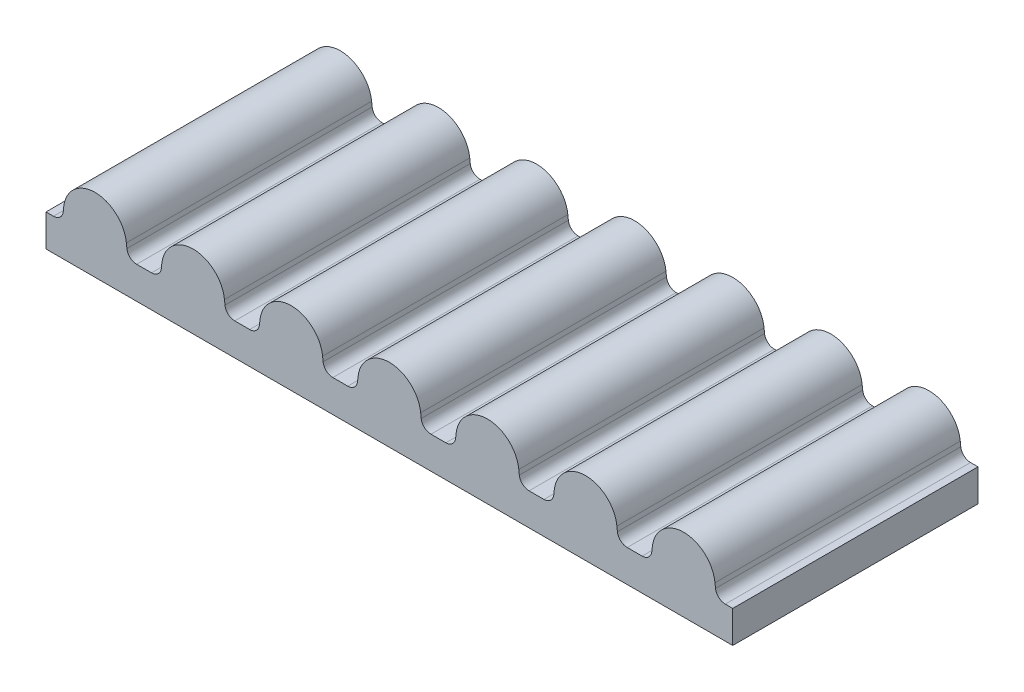
SolidWorks part; units mm, degrees
ref_plane "Front Plane" through (0, 0, 0) normal (0, 0, 1) x (1, 0, 0)
ref_plane "Top Plane" through (0, 0, 0) normal (0, 1, 0) x (1, 0, 0)
ref_plane "Right Plane" through (0, 0, 0) normal (1, 0, 0) x (0, 0, -1)
ref_plane "Plane4" through (0, 0, -10) normal (0, 0, -1) x (-1, 0, 0)
sketch "Sketch1" plane through (0, 0, -10) normal (0, 0, -1) x (-1, 0, 0)
  line L0 (0, 2.62) -> (-0.6084, 2.62)
  line L1 (-1.4036, 3.3322) -> (-1.4455, 3.7119)
  line L2 (-6.5545, 3.7119) -> (-6.5964, 3.3322)
  line L3 (-7.3916, 2.62) -> (-8.6084, 2.62)
  line L4 (-9.4036, 3.3322) -> (-9.4455, 3.7119)
  line L5 (-14.5545, 3.7119) -> (-14.5964, 3.3322)
  line L6 (-15.3916, 2.62) -> (-16.6084, 2.62)
  line L7 (-17.4036, 3.3322) -> (-17.4455, 3.7119)
  line L8 (-22.5545, 3.7119) -> (-22.5964, 3.3322)
  line L9 (-23.3916, 2.62) -> (-24.6084, 2.62)
  line L10 (-25.4036, 3.3322) -> (-25.4455, 3.7119)
  line L11 (-30.5545, 3.7119) -> (-30.5964, 3.3322)
  line L12 (-31.3916, 2.62) -> (-32.6084, 2.62)
  line L13 (-33.4036, 3.3322) -> (-33.4455, 3.7119)
  line L14 (-38.5545, 3.7119) -> (-38.5964, 3.3322)
  line L15 (-39.3916, 2.62) -> (-40.6084, 2.62)
  line L16 (-41.4036, 3.3322) -> (-41.4455, 3.7119)
  line L17 (-46.5545, 3.7119) -> (-46.5964, 3.3322)
  line L18 (-47.3916, 2.62) -> (-48.6084, 2.62)
  line L19 (-49.4036, 3.3322) -> (-49.4455, 3.7119)
  line L20 (-54.5545, 3.7119) -> (-54.5964, 3.3322)
  line L21 (-55.3916, 2.62) -> (-56, 2.62)
  line L22 (-56, 2.62) -> (-56, 0)
  line L23 (-56, 0) -> (0, 0)
  line L24 (0, 0) -> (0, 2.62)
  arc A0 (-0.6084, 2.62) -> (-1.4036, 3.3322) centre (-0.6084, 3.42) cw
  arc A1 (-1.4455, 3.7119) -> (-6.5545, 3.7119) centre (-4, 3.43) ccw
  arc A2 (-6.5964, 3.3322) -> (-7.3916, 2.62) centre (-7.3916, 3.42) cw
  arc A3 (-8.6084, 2.62) -> (-9.4036, 3.3322) centre (-8.6084, 3.42) cw
  arc A4 (-9.4455, 3.7119) -> (-14.5545, 3.7119) centre (-12, 3.43) ccw
  arc A5 (-14.5964, 3.3322) -> (-15.3916, 2.62) centre (-15.3916, 3.42) cw
  arc A6 (-16.6084, 2.62) -> (-17.4036, 3.3322) centre (-16.6084, 3.42) cw
  arc A7 (-17.4455, 3.7119) -> (-22.5545, 3.7119) centre (-20, 3.43) ccw
  arc A8 (-22.5964, 3.3322) -> (-23.3916, 2.62) centre (-23.3916, 3.42) cw
  arc A9 (-24.6084, 2.62) -> (-25.4036, 3.3322) centre (-24.6084, 3.42) cw
  arc A10 (-25.4455, 3.7119) -> (-30.5545, 3.7119) centre (-28, 3.43) ccw
  arc A11 (-30.5964, 3.3322) -> (-31.3916, 2.62) centre (-31.3916, 3.42) cw
  arc A12 (-32.6084, 2.62) -> (-33.4036, 3.3322) centre (-32.6084, 3.42) cw
  arc A13 (-33.4455, 3.7119) -> (-38.5545, 3.7119) centre (-36, 3.43) ccw
  arc A14 (-38.5964, 3.3322) -> (-39.3916, 2.62) centre (-39.3916, 3.42) cw
  arc A15 (-40.6084, 2.62) -> (-41.4036, 3.3322) centre (-40.6084, 3.42) cw
  arc A16 (-41.4455, 3.7119) -> (-46.5545, 3.7119) centre (-44, 3.43) ccw
  arc A17 (-46.5964, 3.3322) -> (-47.3916, 2.62) centre (-47.3916, 3.42) cw
  arc A18 (-48.6084, 2.62) -> (-49.4036, 3.3322) centre (-48.6084, 3.42) cw
  arc A19 (-49.4455, 3.7119) -> (-54.5545, 3.7119) centre (-52, 3.43) ccw
  arc A20 (-54.5964, 3.3322) -> (-55.3916, 2.62) centre (-55.3916, 3.42) cw
extrude "Boss-Extrude1" add sketch "Sketch1" against normal blind 20
